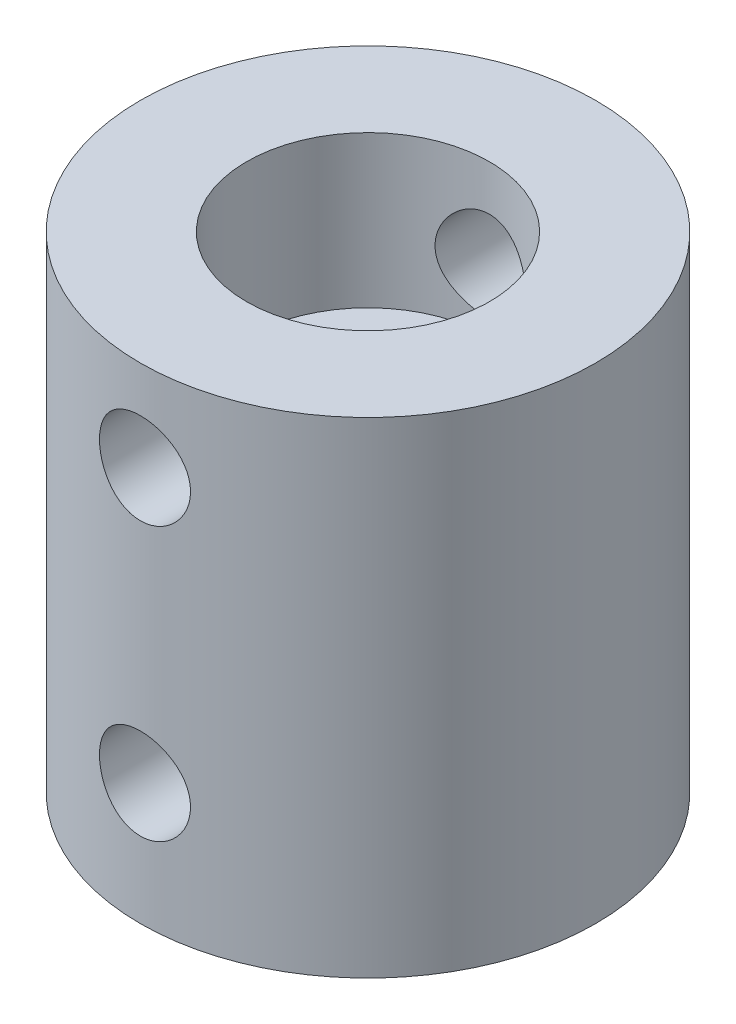
SolidWorks part; units mm, degrees
ref_plane "Front Plane" through (0, 0, 0) normal (0, 0, 1) x (1, 0, 0)
ref_plane "Top Plane" through (0, 0, 0) normal (0, 1, 0) x (1, 0, 0)
ref_plane "Right Plane" through (0, 0, 0) normal (1, 0, 0) x (0, 0, -1)
sketch "Sketch1" plane through (0, 0, 0) normal (0, 1, 0) x (1, 0, 0)
  circle A0 centre (0, 0) radius 7.5
  dimension "D1" = 15
extrude "Boss-Extrude1" add sketch "Sketch1" along normal mid plane 16
sketch "Sketch2" plane through (0, 8, 0) normal (0, 1, 0) x (1, 0, 0)
  circle A0 centre (0, 0) radius 4
  dimension "D1" = 8
extrude "Cut-Extrude1" cut sketch "Sketch2" against normal blind 5
sketch "Sketch3" plane through (0, -8, 0) normal (0, -1, 0) x (1, 0, 0)
  circle A0 centre (0, 0) radius 2.5
  dimension "D1" = 5
extrude "Cut-Extrude2" cut sketch "Sketch3" against normal blind 12
sketch "Sketch4" plane through (0, 0, 0) normal (0, 0, 1) x (1, 0, 0)
  line L0 (0, 8) -> (0, 3) construction
  line L3 (4, 8) -> (-4, 8) construction
  line L4 (-7.5, -8) -> (7.5, -8) construction
  line L5 (-7.5, 3) -> (7.5, 3) construction
  line L6 (-7.5, 8) -> (-7.5, -8) construction
  line L7 (7.5, -8) -> (7.5, 8) construction
  line L8 (-7.5, 0) -> (7.5, 0) construction
  line L9 (0, 0) -> (0, -8) construction
  circle A1 centre (0, -4) radius 1.5
  circle A2 centre (0, 5) radius 1.5
  dimension "D3" = 3
  dimension "D4" = 3
  dimension "D1" = 5
  dimension "D2" = 8
  dimension "D5" = 2
  dimension "D6" = 3
extrude "Cut-Extrude3" cut sketch "Sketch4" against normal through all both and the other way through all
